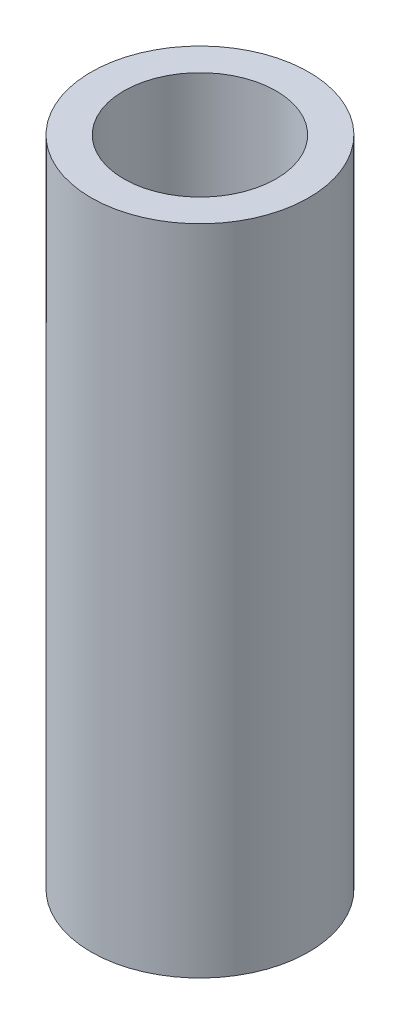
SolidWorks part; units mm, degrees
ref_plane "Front Plane" through (0, 0, 0) normal (0, 0, 1) x (1, 0, 0)
ref_plane "Top Plane" through (0, 0, 0) normal (0, 1, 0) x (1, 0, 0)
ref_plane "Right Plane" through (0, 0, 0) normal (1, 0, 0) x (0, 0, -1)
sketch "Sketch1" plane through (0, 0, 0) normal (0, 1, 0) x (1, 0, 0)
  circle A0 centre (0, 0) radius 5
  dimension "D1" = 10
extrude "Boss-Extrude1" add sketch "Sketch1" along normal blind 30 contours A0
cosmetic thread "Cosmetic Thread2" parameters "D1"=10, "D2"=8.891
sketch "Sketch2" plane through (0, 30, 0) normal (0, 1, 0) x (1, 0, 0)
  circle A0 centre (0, 0) radius 2
  dimension "D1" = 4
extrude "Cut-Extrude1" cut sketch "Sketch2" against normal up to next
sketch "Sketch3" plane through (0, 30, 0) normal (0, 1, 0) x (1, 0, 0)
  circle A0 centre (0, 0) radius 3.5
  dimension "D1" = 7
extrude "Cut-Extrude2" cut sketch "Sketch3" against normal blind 25
cosmetic thread "Cosmetic Thread1" parameters "D1"=10, "D2"=8
